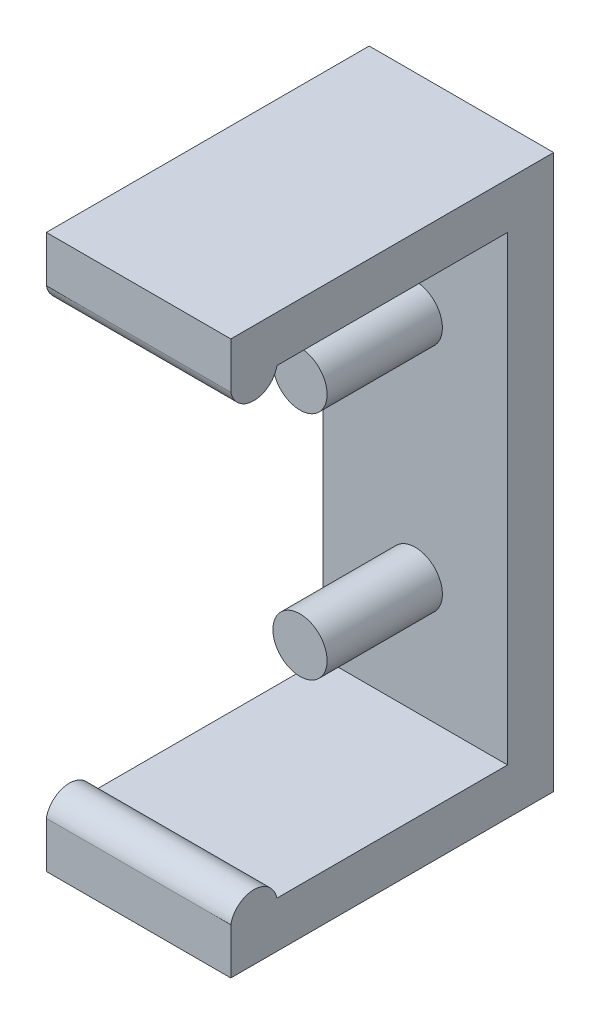
SolidWorks part; units mm, degrees
ref_plane "Front" through (0, 0, 0) normal (0, 0, 1) x (1, 0, 0)
ref_plane "Top" through (0, 0, 0) normal (0, 1, 0) x (1, 0, 0)
ref_plane "Right" through (0, 0, 0) normal (1, 0, 0) x (0, 0, -1)
sketch "Sketch1" plane through (0, 0, 0) normal (0, 0, 1) x (1, 0, 0)
  line L1 (-4, 12) -> (4, 12)
  line L2 (-4, 12) -> (-4, -12)
  line L3 (-4, -12) -> (4, -12)
  line L4 (4, 12) -> (4, -12)
  line L5 (-4, 12) -> (4, -12) construction
  line L6 (-4, -12) -> (4, 12) construction
  point P0 (0, 0)
  dimension "D1" = 24
  dimension "D2" = 8
extrude "Boss-Extrude1" add sketch "Sketch1" along normal blind 2
sketch "Sketch2" plane through (0, 0, 2) normal (0, 0, 1) x (1, 0, 0)
  line L0 (4, -12) -> (4, 12) construction
  line L1 (-4, 12) -> (4, 12)
  line L2 (-4, 12) -> (-4, 10)
  line L3 (-4, 10) -> (4, 10)
  line L4 (4, 12) -> (4, 10)
  line L5 (55, 0) -> (-55, 0) construction
  line L6 (-4, -10) -> (4, -10)
  line L7 (4, -12) -> (4, -10)
  line L8 (-4, -12) -> (4, -12)
  line L9 (-4, -12) -> (-4, -10)
  dimension "D1" = 2
extrude "Boss-Extrude2" add sketch "Sketch2" along normal blind 12
sketch "Sketch3" plane through (4, 0, 0) normal (1, 0, 0) x (0, 0, -1)
  line L0 (-14, 10) -> (-2, 10) construction
  line L1 (-14, 10) -> (-12, 10)
  line L2 (1.1, 0) -> (-1.1, 0) construction
  line L3 (-14, -10) -> (-12, -10)
  arc A0 (-12, 10) -> (-14, 10) centre (-13, 10.201) cw
  arc A1 (-12, -10) -> (-14, -10) centre (-13, -10.201) ccw
  line M8 (-2, -10) -> (-14, -10)
  dimension "D1" = 1.02
  dimension "D2" = 2
extrude "Boss-Extrude4" add sketch "Sketch3" against normal up to surface (8 mm away) contours A1 M8 | A0 L1 up to face at (-4, 0, 7.5)
sketch "Sketch4" plane through (0, 0, 2) normal (0, 0, 1) x (1, 0, 0)
  line L0 (1.1, 0) -> (-1.1, 0) construction
  line L1 (-4, 10) -> (-4, -10) construction
  circle A0 centre (0, 5) radius 1.175
  circle A1 centre (0, -5) radius 1.175
  dimension "D1" = 2.35
  dimension "D2" = 10
  dimension "D3" = 5
  dimension "D4" = 4
extrude "Boss-Extrude5" add sketch "Sketch4" along normal blind 5 contours A1 | A0
